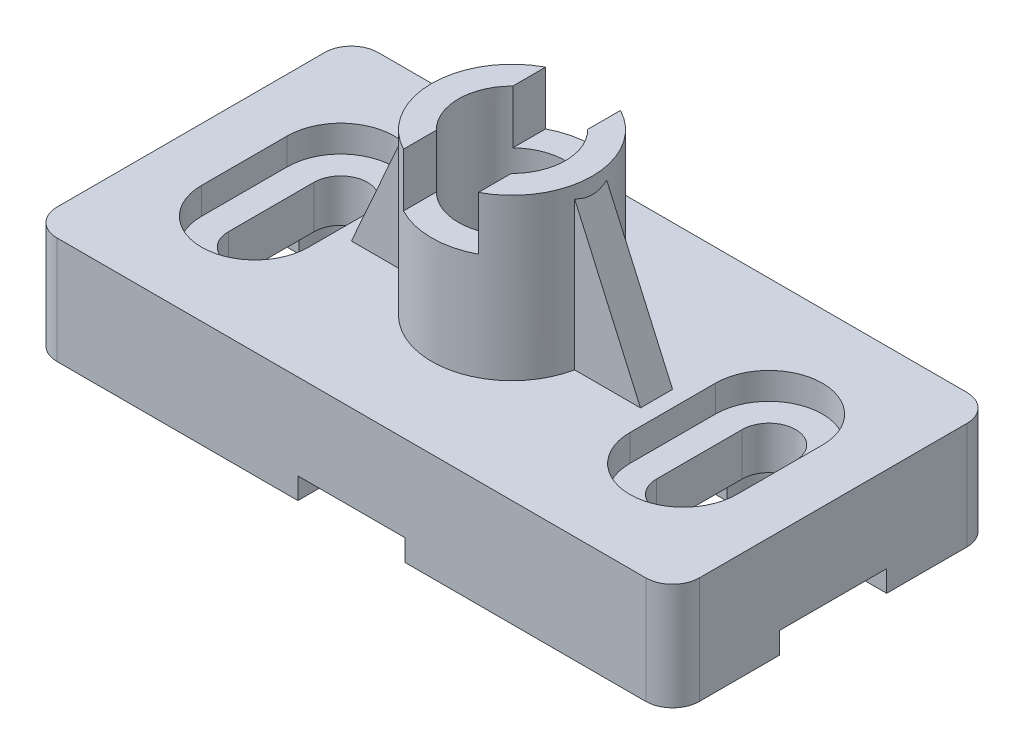
SolidWorks part; units mm, degrees
ref_plane "Front Plane" through (0, 0, 0) normal (0, 0, 1) x (1, 0, 0)
ref_plane "Top Plane" through (0, 0, 0) normal (0, 1, 0) x (1, 0, 0)
ref_plane "Right Plane" through (0, 0, 0) normal (1, 0, 0) x (0, 0, -1)
sketch "Sketch1" plane through (0, 0, 0) normal (0, 0, 1) x (1, 0, 0)
  line L1 (-60, 10) -> (60, 10)
  line L2 (-60, 10) -> (-60, -10)
  line L3 (-60, -10) -> (60, -10)
  line L4 (60, 10) -> (60, -10)
  line L5 (-60, 10) -> (60, -10) construction
  line L6 (-60, -10) -> (60, 10) construction
  point P0 (0, 0)
  dimension "D1" = 120
  dimension "D2" = 20
extrude "Boss-Extrude1" add sketch "Sketch1" along normal blind 60
sketch "Sketch2" plane through (0, 10, 0) normal (0, 1, 0) x (1, 0, 0)
  line L0 (-60, -30) -> (60, -30) construction
  line L1 (-60, -60) -> (-60, 0) construction
  line L2 (60, -60) -> (60, 0) construction
  line L3 (0, 0) -> (0, -60) construction
  line L4 (60, 0) -> (-60, 0) construction
  line L5 (60, -60) -> (-60, -60) construction
  circle A0 centre (0, -30) radius 15
  dimension "D1" = 30
extrude "Boss-Extrude2" add sketch "Sketch2" along normal blind 30
sketch "Sketch3" plane through (0, 40, 0) normal (0, 1, 0) x (1, 0, 0)
  circle A0 centre (0, -30) radius 5
  dimension "D1" = 10
extrude "Cut-Extrude1" cut sketch "Sketch3" against normal blind 76
sketch "Sketch4" plane through (0, 40, 0) normal (0, 1, 0) x (1, 0, 0)
  circle A0 centre (0, -30) radius 10
  dimension "D1" = 20
extrude "Cut-Extrude3" cut sketch "Sketch4" against normal blind 30 contours A0
sketch "Sketch5" plane through (0, -10, 0) normal (0, -1, 0) x (1, 0, 0)
  line L1 (-20, 55) -> (20, 55)
  line L2 (-20, 55) -> (-20, 5)
  line L3 (-20, 5) -> (20, 5)
  line L4 (20, 55) -> (20, 5)
  line L5 (-20, 55) -> (20, 5) construction
  line L6 (-20, 5) -> (20, 55) construction
  point P0 (0, 30)
  dimension "D1" = 50
  dimension "D2" = 40
extrude "Cut-Extrude5" cut sketch "Sketch5" against normal blind 7
sketch "Sketch6" plane through (0, 0, 60) normal (0, 0, 1) x (1, 0, 0)
  line L0 (-60, -10) -> (60, -10) construction
  line L1 (-10, -6) -> (10, -6)
  line L2 (-10, -6) -> (-10, -14)
  line L3 (-10, -14) -> (10, -14)
  line L4 (10, -6) -> (10, -14)
  line L5 (-10, -6) -> (10, -14) construction
  line L6 (-10, -14) -> (10, -6) construction
  point P0 (0, -10)
  dimension "D1" = 20
  dimension "D2" = 8
extrude "Cut-Extrude6" cut sketch "Sketch6" against normal blind 70
sketch "Sketch7" plane through (0, 10, 0) normal (0, 1, 0) x (1, 0, 0)
  line L0 (-40, -22) -> (-40, -38) construction
  line L1 (-30, -22) -> (-30, -38)
  line L2 (-50, -22) -> (-50, -38)
  line L3 (40, -22) -> (40, -38) construction
  line L4 (50, -22) -> (50, -38)
  line L5 (30, -22) -> (30, -38)
  line L6 (0, 0) -> (0, -60) construction
  line L7 (60, -60) -> (-60, -60) construction
  line L8 (-60, -30) -> (60, -30) construction
  line L9 (-60, -60) -> (-60, 0) construction
  line L10 (60, -60) -> (60, 0) construction
  arc A0 (-30, -22) -> (-50, -22) centre (-40, -22) ccw
  arc A1 (-50, -38) -> (-30, -38) centre (-40, -38) ccw
  arc A2 (50, -22) -> (30, -22) centre (40, -22) ccw
  arc A3 (30, -38) -> (50, -38) centre (40, -38) ccw
  point P2 (-40, -30)
  point P7 (40, -30)
  point P25 (0, -30)
  dimension "D1" = 10
  dimension "D4" = 10
  dimension "D2" = 16
  dimension "D3" = 40
  dimension "D5" = 16
  dimension "D6" = 40
extrude "Cut-Extrude7" cut sketch "Sketch7" against normal blind 5
sketch "Sketch9" plane through (0, -10, 0) normal (0, -1, 0) x (1, 0, 0)
  line L0 (-40, 38) -> (-40, 22) construction
  line L1 (-30, 38) -> (-30, 22)
  line L2 (-50, 38) -> (-50, 22)
  line L3 (40, 38) -> (40, 22) construction
  line L4 (50, 38) -> (50, 22)
  line L5 (30, 38) -> (30, 22)
  line L6 (0, 0) -> (0, 60) construction
  line L7 (10, 60) -> (-10, 60) construction
  line L8 (-60, 30) -> (60, 30) construction
  line L9 (-60, 60) -> (-60, 0) construction
  line L10 (60, 60) -> (60, 0) construction
  arc A0 (-30, 38) -> (-50, 38) centre (-40, 38) ccw
  arc A1 (-50, 22) -> (-30, 22) centre (-40, 22) ccw
  arc A2 (50, 38) -> (30, 38) centre (40, 38) ccw
  arc A3 (30, 22) -> (50, 22) centre (40, 22) ccw
  point P2 (-40, 30)
  point P7 (40, 30)
  point P25 (0, 0)
  dimension "D1" = 10
  dimension "D2" = 10
  dimension "D3" = 16
  dimension "D4" = 16
  dimension "D5" = 40
  dimension "D6" = 40
extrude "Cut-Extrude8" cut sketch "Sketch9" against normal blind 7
sketch "Sketch10" plane through (0, 5, 0) normal (0, 1, 0) x (1, 0, 0)
  line L0 (-40, -38) -> (-40, -22) construction
  line L1 (-45, -38) -> (-45, -22)
  line L2 (-35, -38) -> (-35, -22)
  line L3 (0, 0) -> (0, -60) construction
  line L4 (60, -60) -> (-60, -60) construction
  line L5 (40, -38) -> (40, -22) construction
  line L6 (45, -38) -> (45, -22)
  line L7 (35, -38) -> (35, -22)
  arc A0 (-45, -38) -> (-35, -38) centre (-40, -38) ccw
  arc A1 (-35, -22) -> (-45, -22) centre (-40, -22) ccw
  arc A2 (45, -38) -> (35, -38) centre (40, -38) cw
  arc A3 (35, -22) -> (45, -22) centre (40, -22) cw
  point P2 (-40, -30)
  point P12 (0, -30)
  point P15 (40, -30)
  dimension "D1" = 5
  dimension "D2" = 16
  dimension "D3" = 40
extrude "Cut-Extrude9" cut sketch "Sketch10" against normal blind 24
sketch "Sketch11" plane through (0, -10, 0) normal (0, -1, 0) x (1, 0, 0)
  line L0 (60, 60) -> (60, 0) construction
  line L1 (-60, 40) -> (60, 40)
  line L2 (-60, 40) -> (-60, 20)
  line L3 (-60, 20) -> (60, 20)
  line L4 (60, 40) -> (60, 20)
  line L5 (-60, 40) -> (60, 20) construction
  line L6 (-60, 20) -> (60, 40) construction
  point P0 (0, 30)
  dimension "D1" = 20
extrude "Cut-Extrude10" cut sketch "Sketch11" against normal blind 4
ref_plane "Plane1" through (0, 0, 30) normal (0, 0, 1) x (1, 0, 0)
sketch "Sketch12" plane through (0, 0, 30) normal (0, 0, 1) x (1, 0, 0)
  line L0 (-15, 37) -> (-27, 10)
  line L1 (15, 40) -> (-15, 40) construction
  line L2 (-15, 40) -> (-15, 10) construction
  line L3 (0, 0) -> (0, 40) construction
  line L4 (60, 10) -> (-60, 10) construction
  dimension "D1" = 27
  dimension "D2" = 27
rib "Rib10" sketch "Sketch12" sketch "Sketch12" thickness 6 extrusion direction parallel to sketch draft on no parameters "D1"=6
sketch "Sketch13" plane through (0, 0, 30) normal (0, 0, 1) x (1, 0, 0)
  line L0 (15, 37) -> (27, 10)
  line L1 (60, 10) -> (-60, 10) construction
  line L3 (15, 10) -> (15, 40) construction
  dimension "D1" = 27
  dimension "D2" = 27
rib "Rib11" sketch "Sketch13" sketch "Sketch13" thickness 6 extrusion direction parallel to sketch draft on no parameters "D1"=6
fillet "Fillet1" radius 5 4 edges at (60, 0, 0) (60, 0, 60) (-60, 0, 60) (-60, 0, 0)
sketch "Sketch14" plane through (0, 0, 30) normal (0, 0, 1) x (1, 0, 0)
  line L0 (10, 40) -> (-10, 40) construction
  line L1 (-7, 40) -> (7, 40)
  line L2 (-7, 40) -> (-7, 30)
  line L3 (-7, 30) -> (7, 30)
  line L4 (7, 40) -> (7, 30)
  line L5 (15, 40) -> (-15, 40) construction
  dimension "D1" = 7
  dimension "D2" = 14
  dimension "D3" = 10
extrude "Cut-Extrude13" cut sketch "Sketch14" against normal mid plane 40 contours L1 L4 L3 L2
